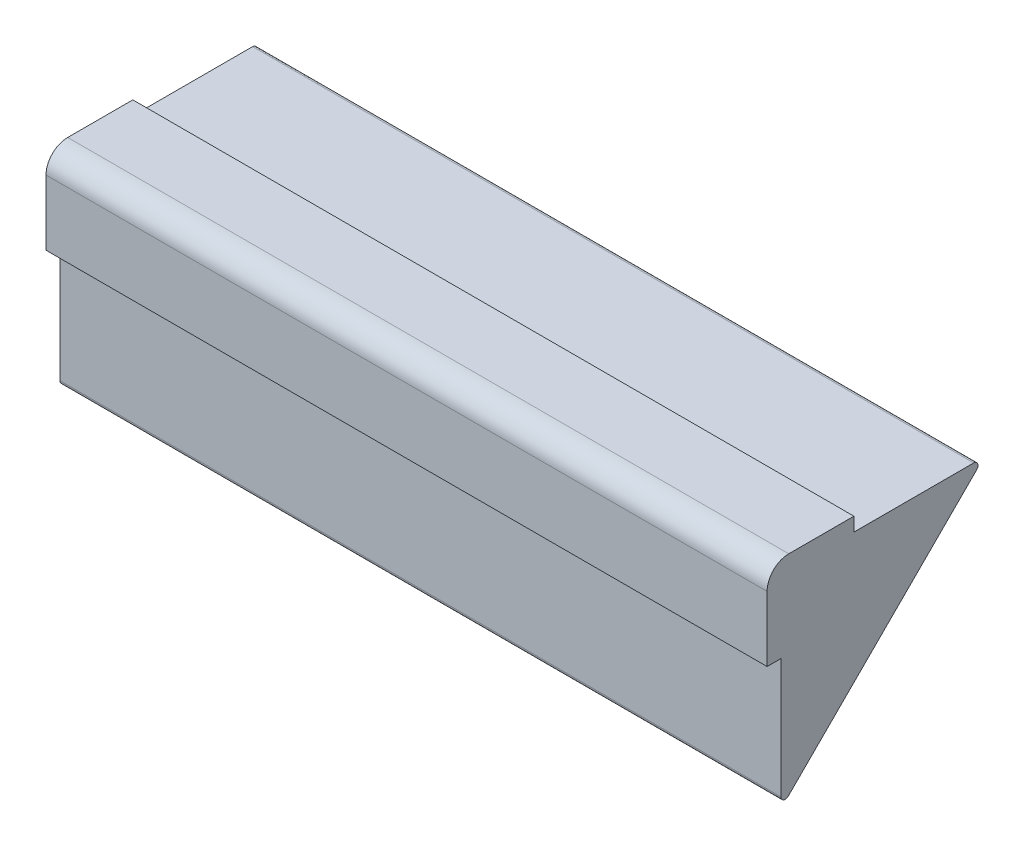
SolidWorks part; units mm, degrees
material "ABS"
ref_plane "Front Plane" through (0, 0, 0) normal (0, 0, 1) x (1, 0, 0)
ref_plane "Top Plane" through (0, 0, 0) normal (0, 1, 0) x (1, 0, 0)
ref_plane "Right Plane" through (0, 0, 0) normal (1, 0, 0) x (0, 0, -1)
sketch "Sketch1" plane through (0, 0, 0) normal (1, 0, 0) x (0, 0, -1)
  line L0 (50, -3.175) -> (3.175, -50) construction
  line L1 (0, 0) -> (20, 0) construction
  line L2 (0, 0) -> (0, -20) construction
  line L3 (0, -20) -> (3.175, -20) construction
  line L4 (20, 0) -> (20, -3.175) construction
  line L7 (20, -3.175) -> (50, -3.175) construction
  line L9 (0, -20) -> (3.175, -20) construction
  line L16 (3.175, -20) -> (3.175, -50) construction
  line L17 (20, 0) -> (20, -3.175) construction
  line L18 (0, -20) -> (0, -5)
  line L19 (5, 0) -> (20, 0)
  line L20 (20, 0) -> (20, -3.175)
  line L21 (20, -3.175) -> (47.5858, -3.175)
  line L22 (48.2929, -4.8821) -> (4.8821, -48.2929)
  line L23 (3.175, -47.5858) -> (3.175, -20)
  line L24 (3.175, -20) -> (0, -20)
  arc A0 (0, -5) -> (5, 0) centre (5, -5) cw
  arc A1 (4.8821, -48.2929) -> (3.175, -47.5858) centre (4.175, -47.5858) cw
  arc A2 (47.5858, -3.175) -> (48.2929, -4.8821) centre (47.5858, -4.175) cw
  dimension "D7" = 5
  dimension "D8" = 1
  dimension "D1" = 3.175
  dimension "D2" = 3.175
  dimension "D3" = 20
  dimension "D4" = 20
  dimension "D5" = 30
  dimension "D6" = 30
extrude "Boss-Extrude1" add sketch "Sketch1" along normal blind 166.124 contours L19 L20 L21 A2 L22 A1 L23 L24 L18 A0
